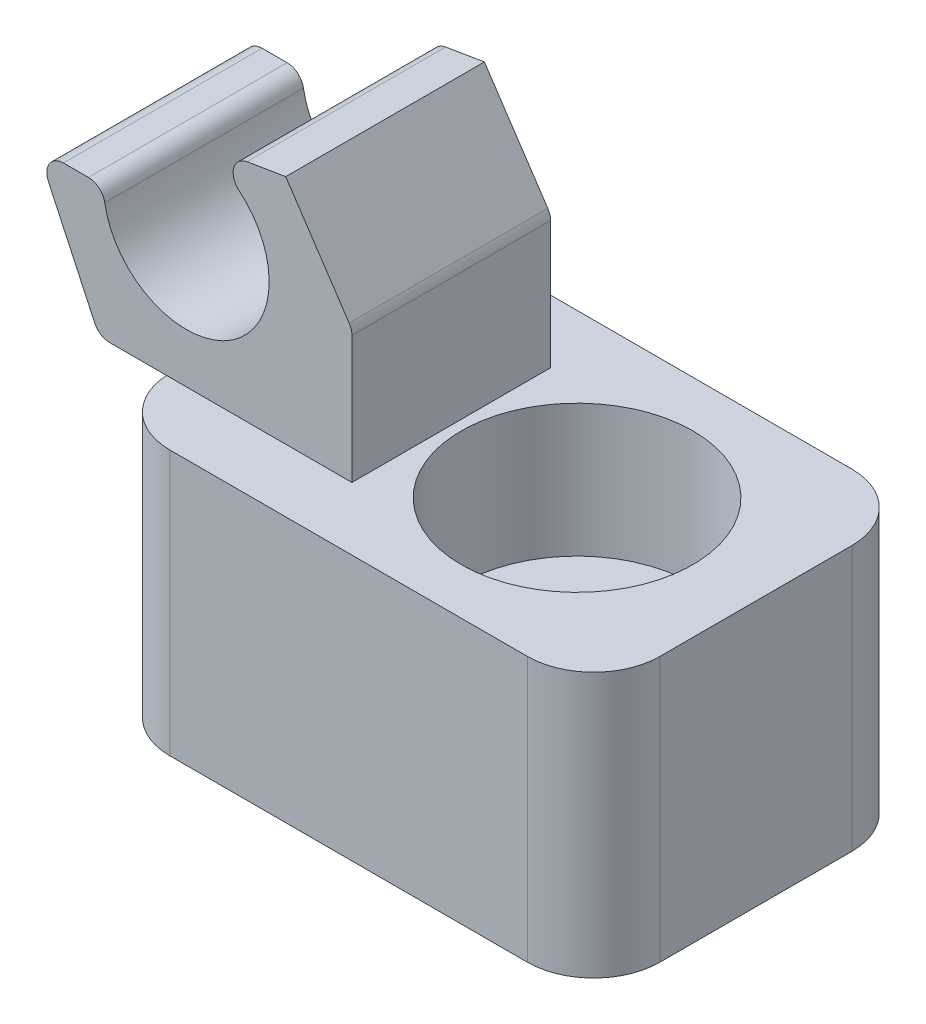
SolidWorks part; units mm, degrees
material "PUR"
ref_plane "Front Plane" through (0, 0, 0) normal (0, 0, 1) x (1, 0, 0)
ref_plane "Top Plane" through (0, 0, 0) normal (0, 1, 0) x (1, 0, 0)
ref_plane "Right Plane" through (0, 0, 0) normal (1, 0, 0) x (0, 0, -1)
sketch "Sketch1" plane through (0, 0, 0) normal (0, 1, 0) x (1, 0, 0)
  line L1 (-5.4, -4.9) -> (5.4, -4.9)
  line L2 (-7.4, -2.9) -> (-7.4, 2.9)
  line L3 (-5.4, 4.9) -> (5.4, 4.9)
  line L4 (7.4, -2.9) -> (7.4, 2.9)
  line L5 (-7.4, -4.9) -> (7.4, 4.9) construction
  line L6 (-7.4, 4.9) -> (7.4, -4.9) construction
  arc A0 (5.4, 4.9) -> (7.4, 2.9) centre (5.4, 2.9) cw
  arc A1 (5.4, -4.9) -> (7.4, -2.9) centre (5.4, -2.9) ccw
  arc A2 (-5.4, -4.9) -> (-7.4, -2.9) centre (-5.4, -2.9) cw
  arc A3 (-7.4, 2.9) -> (-5.4, 4.9) centre (-5.4, 2.9) cw
  point P0 (0, 0)
  dimension "D3" = 2
  dimension "D1" = 9.8
  dimension "D2" = 14.8
extrude "Boss-Extrude1" add sketch "Sketch1" along normal blind 8
sketch "Sketch2" plane through (0, 8, 0) normal (0, 1, 0) x (1, 0, 0)
  line L0 (2, 0) -> (0, 0) construction
  circle A0 centre (2, 0) radius 3.5
  dimension "D1" = 7
  dimension "D2" = 2
extrude "Cut-Extrude1" cut sketch "Sketch2" against normal blind 4
sketch "Sketch3" plane through (0, 4, 0) normal (0, 1, 0) x (1, 0, 0)
  circle A0 centre (2, 0) radius 1.8
  circle A1 centre (2, 0) radius 3.5
  circle A2 centre (2, 0) radius 3.5 construction
  dimension "D2" = 3.6
  dimension "D1" = 0
extrude "Cut-Extrude2" cut sketch "Sketch3" against normal blind 4
sketch "Sketch4" plane through (0, 0, 0) normal (0, 0, 1) x (1, 0, 0)
  line L0 (-1.8, 8) -> (-1.8, 12)
  line L1 (-5.4, 8) -> (5.4, 8) construction
  line L2 (-1.8, 12) -> (-3.8, 15)
  line L3 (-7.4, 8) -> (-1.8, 8)
  line L4 (-7.4, 8) -> (-7.4, 0) construction
  line L5 (-7.4, 8) -> (-9.4348, 8)
  line L6 (-6.8, 12) -> (-11.3, 12) construction
  line L7 (-9.4348, 8) -> (-11.3, 12)
  line L8 (-11.3, 12) -> (-9.3, 12)
  line L9 (-3.8, 15) -> (-6.8, 14.5)
  circle A0 centre (-6.8, 12) radius 2.5 construction
  arc A1 (-9.3, 12) -> (-6.8, 14.5) centre (-6.8, 12) ccw
  point P15 (0, 0)
  point P17 (-10.9876, 12)
  dimension "D5" = 5
  dimension "D1" = 5.6
  dimension "D2" = 4
  dimension "D3" = 7
  dimension "D4" = 2
  dimension "D6" = 5
  dimension "D7" = 4
  dimension "D8" = 115
  dimension "D9" = 2
extrude "Boss-Extrude2" add sketch "Sketch4" along normal blind 3 and the other way blind 3 contours A1 L8 L7 L5 L3 L0 L2 L9
fillet "Fillet1" radius 0.5 5 edges at (-1.8, 12, 0) (-9.3, 12, 0) (-6.8, 14.5, 0) (-9.4348, 8, 0) (-11.3, 12, 0)
